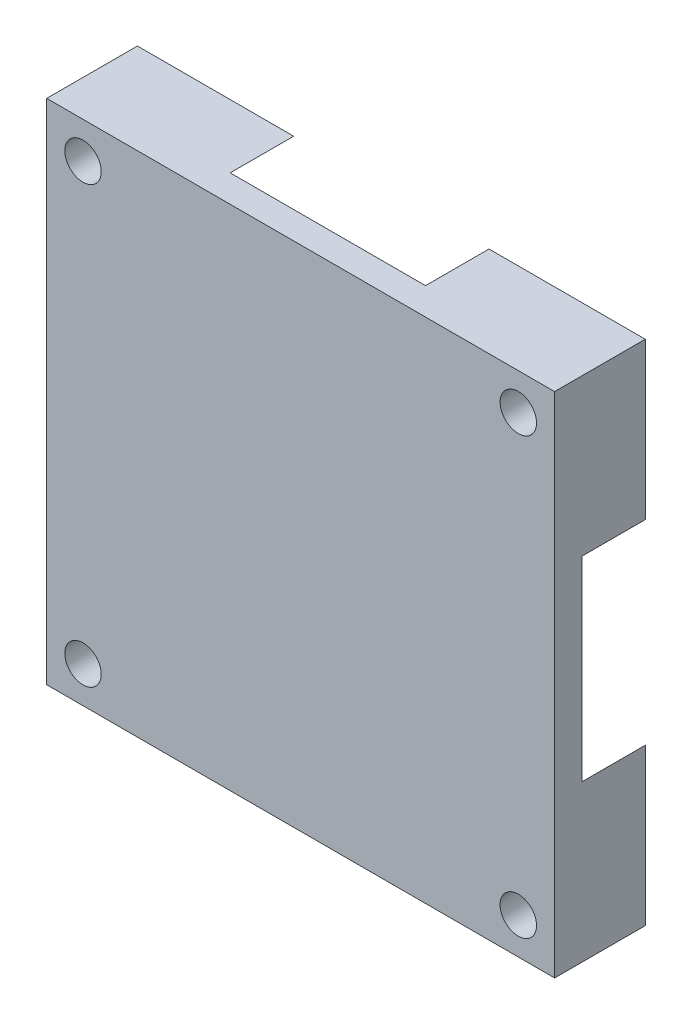
SolidWorks part; units mm, degrees
ref_plane "Front Plane" through (0, 0, 0) normal (0, 0, 1) x (1, 0, 0)
ref_plane "Top Plane" through (0, 0, 0) normal (0, 1, 0) x (1, 0, 0)
ref_plane "Right Plane" through (0, 0, 0) normal (1, 0, 0) x (0, 0, -1)
sketch "Sketch1" plane through (0, 0, 0) normal (0, 0, 1) x (1, 0, 0)
  line L0 (-38.1, 0) -> (0, 0) construction
  line L1 (0, 0) -> (-30.48, 30.48) construction
  line L3 (35.56, -35.56) -> (-35.56, -35.56)
  line L4 (35.56, -35.56) -> (35.56, 35.56)
  line L5 (35.56, 35.56) -> (-35.56, 35.56)
  line L6 (-35.56, -35.56) -> (-35.56, 35.56)
  line L7 (35.56, -35.56) -> (-35.56, 35.56) construction
  line L8 (35.56, 35.56) -> (-35.56, -35.56) construction
  circle A0 centre (0, 0) radius 38.1 construction
  circle A1 centre (-30.48, 30.48) radius 2.5527 construction
  dimension "D1" = 76.2
  dimension "D2" = 5.1054
  dimension "D3" = 45
  dimension "D4" = 5.08
  dimension "D5" = 30.48
extrude "Boss-Extrude1" add sketch "Sketch1" along normal blind 12.7
sketch "Sketch2" plane through (0, 0, 0) normal (0, 0, -1) x (-1, 0, 0)
  circle A0 centre (0, 0) radius 38.1
  dimension "D1" = 76.2
extrude "Cut-Extrude1" cut sketch "Sketch2" against normal blind 8.89
hole_wizard "#7 (0.201) Diameter Hole1" positions "Sketch4" profile "Sketch3" hole size "#7" standard "Ansi Inch"
sketch "Sketch4" plane through (0, 0, 12.7) normal (0, 0, 1) x (1, 0, 0)
  line L0 (-30.48, 30.48) -> (30.48, -30.48) construction
  line L3 (30.48, 30.48) -> (-30.48, -30.48) construction
  point P0 (30.48, 30.48)
  point P1 (-30.48, 30.48)
  point P3 (-30.48, -30.48)
  point P5 (30.48, -30.48)
  dimension "D1" = 60.96
  dimension "D2" = 60.96
sketch "Sketch3" plane through (30.48, 30.48, 12.7) normal (1, 0, 0) x (0, -1, 0)
  line L0 (0, 0) -> (0, 33.2838)
  line L1 (0, 33.2838) -> (2.5527, 31.75)
  line L2 (2.5527, 31.75) -> (2.5527, 0)
  line L5 (2.5527, 0) -> (0, 0)
  line L10 (0, 33.2838) -> (-2.5527, 31.75) construction
  line L11 (0, -6.35) -> (0, 107.95) construction
  dimension "Hole Dia." = 5.1054
  dimension "Hole Depth" = 31.75
  dimension "Drill Angle" = 118
